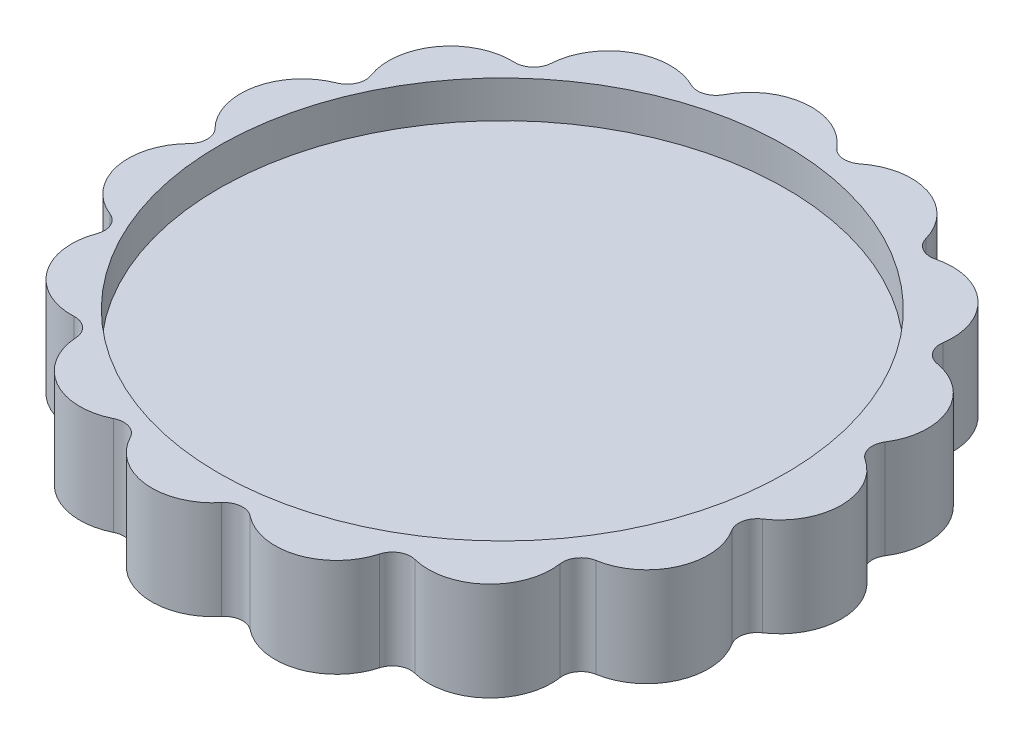
SolidWorks part; units mm, degrees
ref_plane "前视基准面" through (0, 0, 0) normal (0, 0, 1) x (1, 0, 0)
ref_plane "上视基准面" through (0, 0, 0) normal (0, 1, 0) x (1, 0, 0)
ref_plane "右视基准面" through (0, 0, 0) normal (1, 0, 0) x (0, 0, -1)
sketch "草图1" plane through (0, 0, 0) normal (0, 1, 0) x (1, 0, 0)
  circle A0 centre (0, 0) radius 22.5
  dimension "D1" = 45
extrude "凸台-拉伸1" add sketch "草图1" along normal blind 8
sketch "草图3" plane through (0, 8, 0) normal (0, 1, 0) x (1, 0, 0)
  circle A0 centre (22.5, 0) radius 5
  circle A1 centre (0, 0) radius 22.5 construction
  dimension "D1" = 10
extrude "凸台-拉伸3" add sketch "草图3" against normal blind 8
pattern_circular "阵列(圆周)1" count 15 over 360 about axis through (0.618, 0, 0) along (0, 1, 0) of "凸台-拉伸3"
fillet "圆角1" radius 1.5 15 edges at (19.612, 4, -13.8) (12.357, 4, -20.3325) (3.0721, 4, -23.3493) (-6.6371, 4, -22.3288) (-15.0918, 4, -17.4475) (-20.8301, 4, -9.5493) (-22.8599, 4, 0) (-20.8301, 4, 9.5493) (-6.6371, 4, 22.3288) (3.0721, 4, 23.3493) (12.357, 4, 20.3325) (19.612, 4, 13.8) (23.5829, 4, 4.8813) (23.5829, 4, -4.8813) (-15.0918, 4, 17.4475)
sketch "草图6" plane through (0, 8, 0) normal (0, 1, 0) x (1, 0, 0)
  circle A0 centre (0, 0) radius 23
sketch "草图8" plane through (0, 8, 0) normal (0, 1, 0) x (1, 0, 0)
extrude "切除-拉伸1" cut sketch "草图6" against normal blind 3
